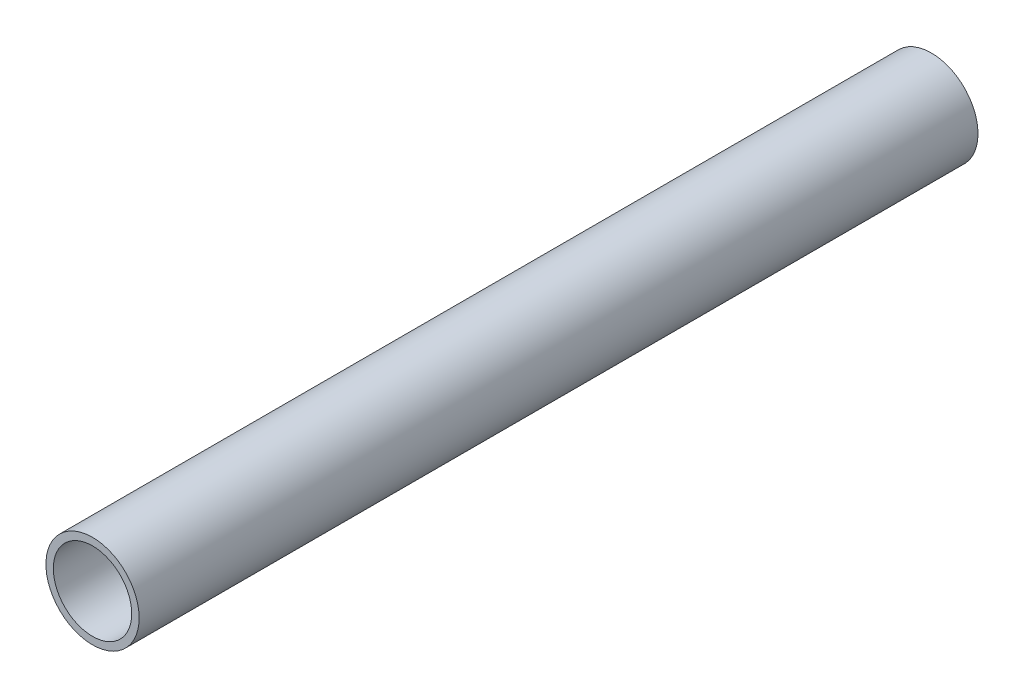
SolidWorks part; units mm, degrees
material "Plain Carbon Steel"
ref_plane "Front Plane" through (0, 0, 0) normal (0, 0, 1) x (1, 0, 0)
ref_plane "Top Plane" through (0, 0, 0) normal (0, 1, 0) x (1, 0, 0)
ref_plane "Right Plane" through (0, 0, 0) normal (1, 0, 0) x (0, 0, -1)
sketch "Sketch1" plane through (0, 0, 0) normal (0, 0, 1) x (1, 0, 0)
  circle A2 centre (0, 0) radius 50.8
  circle A3 centre (0, 0) radius 42.7355
extrude "Boss-Extrude1" add sketch "Sketch1" along normal blind 914.4
